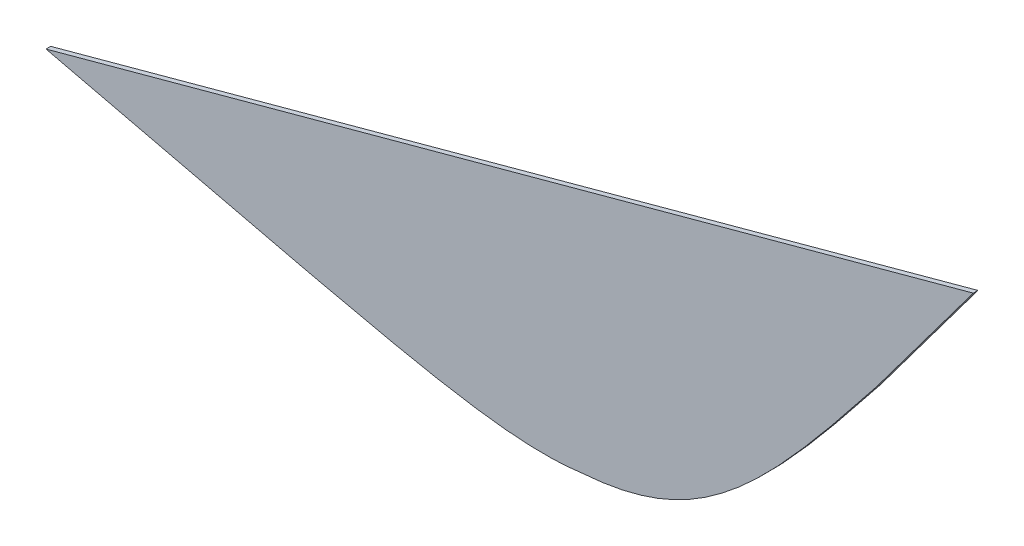
SolidWorks part; units mm, degrees
material "Сталь 3 ГОСТ 535-88"
ref_plane "Спереди" through (0, 0, 0) normal (0, 0, 1) x (1, 0, 0)
ref_plane "Сверху" through (0, 0, 0) normal (0, 1, 0) x (1, 0, 0)
ref_plane "Справа" through (0, 0, 0) normal (1, 0, 0) x (0, 0, -1)
sketch "Эскиз6" plane through (0, 0, 0) normal (0, 0, 1) x (1, 0, 0)
  line L0 (159.9974, 144.492) -> (210.3478, 69.0364)
  line L1 (226, 39.0364) -> (214.96, 39.0364) construction
  line L2 (718.4837, 179.0364) -> (700.0837, 179.0364) construction
  line L3 (-400.6671, 126.9485) -> (-400.6671, 86.2896)
  line L4 (-400.6671, 86.2896) -> (-645.3521, 86.2896)
  line L5 (-645.3521, 86.2896) -> (-645.3521, 210.6437)
  line L6 (217.4722, 117.8535) -> (217.4722, 86.841)
  line L7 (217.4722, 86.841) -> (645.9046, 86.841)
  line L8 (645.9046, 86.841) -> (645.9046, 419.9385)
  line L9 (645.9046, 419.9385) -> (589.6226, 419.9385)
  line L10 (129.7147, 135.0472) -> (134.503, 135.0472)
  line L11 (134.503, 135.0472) -> (145.3144, 146.0283)
  line L12 (145.3144, 146.0283) -> (149.5928, 146.0283)
  line L13 (170.621, 146.0283) -> (176.2959, 146.0283)
  line L14 (176.2959, 146.0283) -> (187.0167, 162.1065)
  line L15 (187.0167, 162.1065) -> (192.487, 162.1065)
  line L16 (213.5078, 162.1065) -> (217.9363, 162.1065)
  line L17 (217.9363, 162.1065) -> (223.9551, 178.9116)
  line L18 (223.9551, 178.9116) -> (227.8328, 178.9116)
  line L19 (248.8496, 178.9116) -> (253.3366, 178.9116)
  line L20 (253.3366, 178.9116) -> (259.6787, 199.2242)
  line L21 (259.6787, 199.2242) -> (263.7828, 199.2242)
  line L22 (284.7878, 199.2242) -> (289.7762, 199.2242)
  line L23 (289.7762, 199.2242) -> (293.1158, 221.4014)
  line L24 (293.1158, 221.4014) -> (296.4561, 221.4014)
  line L25 (317.4517, 221.4014) -> (322.271, 221.4014)
  line L26 (322.271, 221.4014) -> (329.3569, 250.2967)
  line L27 (329.3569, 250.2967) -> (332.468, 250.2967)
  line L28 (353.4646, 250.2967) -> (357.631, 250.2967)
  line L29 (357.631, 250.2967) -> (360.3764, 277.7773)
  line L30 (360.3764, 277.7773) -> (363.766, 277.7773)
  line L31 (384.761, 277.7773) -> (388.2696, 277.7773)
  line L32 (388.2696, 277.7773) -> (388.2696, 302.6757)
  line L33 (388.2696, 302.6757) -> (390.7857, 302.6757)
  line L34 (411.8473, 302.6757) -> (414.8074, 302.6757)
  line L35 (414.8074, 302.6757) -> (417.8424, 333.0542)
  line L36 (417.8424, 333.0542) -> (421.762, 333.0542)
  line L37 (442.8969, 333.0542) -> (446.8367, 333.0542)
  line L38 (446.8367, 333.0542) -> (450.1833, 366.5298)
  line L39 (450.1833, 366.5298) -> (453.9049, 366.5298)
  line L40 (475.1272, 366.5298) -> (479.7136, 366.5298)
  line L41 (479.7136, 366.5298) -> (483.3744, 403.1486)
  line L42 (483.3744, 403.1486) -> (488.3363, 403.1486)
  line L43 (509.572, 403.1486) -> (512.6284, 403.1486)
  line L44 (512.6284, 403.1486) -> (510.988, 431.9207)
  line L45 (510.988, 431.9207) -> (513.6642, 431.9207)
  line L46 (535.0047, 431.9207) -> (538.0588, 431.9207)
  line L47 (538.0588, 431.9207) -> (531.6588, 456.6414)
  line L48 (531.6588, 456.6414) -> (535.1524, 456.6414)
  line L49 (556.5302, 456.6414) -> (572.9497, 456.6414)
  line L50 (572.9497, 456.6414) -> (633.4819, 487.5397)
  line L51 (633.4819, 487.5397) -> (740, 487.5397)
  line L52 (740, 487.5397) -> (740, 60.0335)
  line L53 (740, 60.0335) -> (700, 60.0335)
  line L54 (700, 60.0335) -> (700, 0.0364)
  line L55 (700, 0.0364) -> (-700, 0.0364)
  line L56 (-700, 0.0364) -> (-700, 60.0335)
  line L57 (-700, 60.0335) -> (-740, 60.0335)
  line L58 (-740, 60.0335) -> (-740, 250.6437)
  line L59 (-740, 250.6437) -> (-730, 260.6437)
  line L60 (-730, 260.6437) -> (-638.0228, 260.6437)
  line L61 (-638.0228, 260.6437) -> (-612.6272, 247.9974)
  line L62 (-612.6272, 247.9974) -> (-608.3433, 247.9974)
  line L63 (-587.2113, 247.9974) -> (-583.7724, 247.9974)
  line L64 (-583.7724, 247.9974) -> (-563.198, 232.0913)
  line L65 (-563.198, 232.0913) -> (-560.5785, 232.0913)
  line L66 (-539.3589, 232.0913) -> (-535.6831, 232.0913)
  line L67 (-535.6831, 232.0913) -> (-518.1938, 218.1693)
  line L68 (-518.1938, 218.1693) -> (-515.5563, 218.1693)
  line L69 (-494.2585, 218.1192) -> (-491.1074, 218.1192)
  line L70 (-491.1074, 218.1192) -> (-478.9346, 206.3677)
  line L71 (-478.9346, 206.3677) -> (-477.0025, 206.3677)
  line L72 (-455.6816, 206.3677) -> (-451.8259, 206.3677)
  line L73 (-451.8259, 206.3677) -> (-436.7193, 193.0631)
  line L74 (-436.7193, 193.0631) -> (-433.8145, 193.0631)
  line L75 (-412.5623, 193.0631) -> (-408.8172, 193.0631)
  line L76 (-408.8172, 193.0631) -> (-390.2035, 180.5615)
  line L77 (-390.2035, 180.5615) -> (-386.7357, 180.5615)
  line L78 (-365.3543, 180.5615) -> (-361.3994, 180.5615)
  line L79 (-361.3994, 180.5615) -> (-348.9375, 170.5686)
  line L80 (-348.9375, 170.5686) -> (-346.1252, 170.5686)
  line L81 (-324.7499, 170.5686) -> (-321.4624, 170.5686)
  line L82 (-321.4624, 170.5686) -> (-307.719, 159.9631)
  line L83 (-307.719, 159.9631) -> (-304.4249, 159.9631)
  line L84 (-283.0946, 159.9631) -> (-278.741, 159.9631)
  line L85 (-278.741, 159.9631) -> (-258.7483, 149.6686)
  line L86 (-258.7483, 149.6686) -> (-254.9859, 149.6686)
  line L87 (-233.6439, 149.6686) -> (-230.797, 149.6686)
  line L88 (-230.797, 149.6686) -> (-216.8081, 140.8158)
  line L89 (-216.8081, 140.8158) -> (-214.3359, 140.8158)
  line L90 (-193.053, 140.8158) -> (-189.1396, 140.8158)
  line L91 (-189.1396, 140.8158) -> (-172.2177, 133.3984)
  line L92 (-172.2177, 133.3984) -> (-169.0298, 133.3984)
  line L93 (-147.7841, 133.3984) -> (-144.7309, 133.3984)
  line L94 (-144.7309, 133.3984) -> (-135.5541, 127.5909)
  line L95 (-135.5541, 127.5909) -> (-132.839, 127.8707)
  line L96 (-111.6873, 127.886) -> (-107.1839, 127.886)
  line L97 (-107.1839, 127.886) -> (-97.4501, 123.6194)
  line L98 (-97.4501, 123.6194) -> (-94.273, 123.6194)
  line L99 (-73.1729, 123.6194) -> (-70.5293, 123.6194)
  line L100 (-70.5293, 123.6194) -> (-58.3851, 121.2414)
  line L101 (-58.3851, 121.2414) -> (-55.027, 121.2414)
  line L102 (-33.981, 121.2414) -> (-17.5651, 120.7257)
  line L103 (3.4497, 120.7248) -> (6.5797, 120.7248)
  line L104 (6.5797, 120.7248) -> (24.5339, 122.2358)
  line L105 (24.5339, 122.2358) -> (27.2628, 122.2358)
  line L106 (48.3493, 122.2358) -> (52.6456, 122.2358)
  line L107 (52.6456, 122.2358) -> (66.9754, 126.8281)
  line L108 (66.9754, 126.8281) -> (70.0874, 126.8281)
  line L109 (91.1524, 126.8281) -> (95.4501, 126.8281)
  line L110 (95.4501, 126.8281) -> (105.3995, 135.0472)
  line L111 (105.3995, 135.0472) -> (108.7154, 135.0472)
  line L112 (119.1051, 132.5605) -> (165.9674, 87.0364)
  line L113 (80.6544, 126.6192) -> (124.3478, 87.0364)
  line L114 (37.7151, 121.1307) -> (84.3478, 87.0364)
  line L115 (187, 57.0364) -> (167.17, 57.0364) construction
  line L116 (140, 57.0364) -> (128.96, 57.0364) construction
  line L117 (100, 57.0364) -> (88.96, 57.0364) construction
  arc A0 (-645.3521, 210.6437) -> (-400.6671, 126.9485) centre (-294.2151, 837.682) ccw
  arc A1 (217.4722, 117.8535) -> (589.6226, 419.9385) centre (-115.7769, 908.672) ccw
  circle A2 centre (-690, 210.6437) radius 7.5
  circle A3 centre (-690, 86.841) radius 7.5
  circle A4 centre (690, 410.9067) radius 7.5
  circle A5 centre (690, 86.841) radius 7.5
  circle A6 centre (0, 86.841) radius 7.5
  arc A7 (149.5928, 146.0283) -> (170.4934, 143.8205) centre (159.9974, 144.492) ccw
  arc A8 (170.4934, 143.8205) -> (170.621, 146.0283) centre (160.132, 145.527) ccw
  arc A9 (192.5222, 161.4078) -> (213.5078, 162.1065) centre (203.0218, 161.553) ccw
  arc A10 (227.861, 178.3411) -> (248.8496, 178.9116) centre (238.3618, 178.3905) ccw
  arc A11 (263.788, 199.1538) -> (284.7878, 199.2242) centre (274.2878, 199.2122) ccw
  arc A12 (296.4561, 221.4014) -> (317.4517, 221.4014) centre (306.9539, 221.5851) ccw
  arc A13 (332.468, 250.2967) -> (353.4646, 250.2967) centre (342.9663, 250.0653) ccw
  arc A14 (363.766, 277.7773) -> (384.7582, 277.7092) centre (374.261, 277.4219) ccw
  arc A15 (390.7857, 302.6757) -> (411.7533, 301.8481) centre (401.2843, 302.6377) ccw
  arc A16 (421.762, 333.0542) -> (442.5956, 331.3857) centre (432.2574, 333.2017) ccw
  arc A17 (453.9049, 366.5298) -> (474.6161, 363.9727) centre (464.3993, 366.3755) ccw
  arc A18 (488.3363, 403.1486) -> (508.9775, 400.4796) centre (498.8312, 403.1622) ccw
  arc A19 (513.6642, 431.9207) -> (534.1303, 428.2462) centre (524.1492, 431.4868) ccw
  arc A20 (535.1524, 456.6414) -> (555.5133, 452.407) centre (545.6202, 455.9058) ccw
  arc A21 (-601.1014, 237.8145) -> (-587.2113, 247.9974) centre (-597.7085, 247.7513) ccw
  arc A22 (-553.2804, 222.3244) -> (-539.3589, 232.0913) centre (-549.8583, 232.2517) ccw
  arc A23 (-508.9874, 208.5183) -> (-494.2585, 218.1192) centre (-504.7606, 218.1321) ccw
  arc A24 (-469.748, 196.6324) -> (-455.6816, 206.3677) centre (-466.1821, 206.51) ccw
  arc A25 (-426.765, 184.167) -> (-412.5623, 193.0631) centre (-423.0243, 193.9804) ccw
  arc A26 (-379.6878, 171.27) -> (-365.3543, 180.5615) centre (-375.8456, 181.0444) ccw
  arc A27 (-339.5262, 160.8306) -> (-324.7499, 170.5686) centre (-335.2506, 170.4225) ccw
  arc A28 (-298.5163, 150.924) -> (-283.0946, 159.9631) centre (-293.5932, 160.1998) ccw
  arc A29 (-249.573, 140.2853) -> (-233.6439, 149.6686) centre (-244.1369, 149.2692) ccw
  arc A30 (-210.032, 132.8776) -> (-193.053, 140.8158) centre (-203.5474, 141.135) ccw
  arc A31 (-166.0837, 126.2903) -> (-147.7841, 133.3984) centre (-158.2825, 133.3164) ccw
  arc A32 (-131.5368, 123.2265) -> (-111.6873, 127.886) centre (-122.1855, 127.999) ccw
  arc A33 (-93.6949, 120.6889) -> (-73.1729, 123.6194) centre (-83.6701, 123.808) ccw
  arc A34 (-54.9241, 119.973) -> (-33.981, 121.2414) centre (-44.4786, 121.0373) ccw
  arc A35 (-17.5394, 120.0593) -> (3.4497, 120.7248) centre (-7.0426, 120.32) ccw
  arc A36 (27.2628, 122.2358) -> (48.2029, 120.439) centre (37.7151, 121.1307) ccw
  arc A37 (48.2029, 120.439) -> (48.3493, 122.2358) centre (37.8493, 122.1868) ccw
  arc A38 (70.0874, 126.8281) -> (91.0173, 124.9276) centre (80.5201, 125.5228) ccw
  arc A39 (91.0173, 124.9276) -> (91.1524, 126.8281) centre (80.6544, 126.6192) ccw
  arc A40 (108.7191, 134.67) -> (108.7137, 134.1424) centre (119.2134, 134.2996) ccw
  arc A41 (108.7137, 134.1424) -> (129.6124, 132.8403) centre (119.1051, 132.5605) ccw
  arc A42 (129.6124, 132.8403) -> (129.7095, 134.6179) centre (119.2134, 134.2996) ccw
  spline S0 degree 2 poles (129.7095, 134.6179) (129.7146, 134.7763) (129.715, 134.9349) (129.7152, 134.991) (129.7147, 135.0472) knots 5070.278971 5070.278971 5070.278971 5070.312198 5070.312198 5070.324013 5070.324013 5070.324013 weights 0.987871 0.993804 1 0.997797 0.995627
  spline S1 degree 2 poles (192.487, 162.1065) (192.49, 161.9315) (192.4988, 161.7566) (192.5076, 161.582) (192.5222, 161.4078) knots 5161.397645 5161.397645 5161.397645 5161.4343 5161.4343 5161.470885 5161.470885 5161.470885 weights 0.986649 0.993165 1 0.993178 0.986675
  spline S2 degree 2 poles (227.8328, 178.9116) (227.8352, 178.8065) (227.8397, 178.7015) (227.8473, 178.5211) (227.861, 178.3411) knots 5221.024769 5221.024769 5221.024769 5221.046824 5221.046824 5221.084599 5221.084599 5221.084599 weights 0.991891 0.995888 1 0.992956 0.986252
  spline S3 degree 2 poles (263.7828, 199.2242) (263.7854, 199.189) (263.788, 199.1538) knots 5284.416642 5284.416642 5284.416642 5284.423983 5284.423983 5284.423983 weights 0.988702 0.987387 0.986086
  spline S4 degree 2 poles (384.7582, 277.7092) (384.7597, 277.7432) (384.761, 277.7773) knots 5520.678201 5520.678201 5520.678201 5520.685284 5520.685284 5520.685284 weights 0.986308 0.987566 0.988836
  spline S5 degree 2 poles (411.7533, 301.8481) (411.7825, 302.0383) (411.8048, 302.2294) (411.8308, 302.4521) (411.8473, 302.6757) knots 5583.838669 5583.838669 5583.838669 5583.878882 5583.878882 5583.925685 5583.925685 5583.925685 weights 0.985388 0.992502 1 0.991273 0.983066
  spline S6 degree 2 poles (442.5956, 331.3857) (442.6493, 331.5886) (442.6949, 331.7935) (442.8339, 332.4178) (442.8969, 333.0542) knots 5652.338493 5652.338493 5652.338493 5652.382299 5652.382299 5652.513577 5652.513577 5652.513577 weights 0.984119 0.991832 1 0.975522 0.955135
  spline S7 degree 2 poles (474.6161, 363.9727) (474.6856, 364.1821) (474.7463, 364.3942) (475.0463, 365.4426) (475.1272, 366.5298) knots 5724.520113 5724.520113 5724.520113 5724.566104 5724.566104 5724.78602 5724.78602 5724.78602 weights 0.983351 0.991424 1 0.958994 0.92947
  spline S8 degree 2 poles (508.9775, 400.4796) (509.053, 400.6876) (509.1198, 400.8985) (509.4681, 401.9992) (509.572, 403.1486) knots 5801.380203 5801.380203 5801.380203 5801.426335 5801.426335 5801.658582 5801.658582 5801.658582 weights 0.983302 0.991398 1 0.956695 0.926195
  spline S9 degree 2 poles (534.1303, 428.2462) (534.2267, 428.4667) (534.3129, 428.6913) (534.9125, 430.2523) (535.0047, 431.9207) knots 5866.3178 5866.3178 5866.3178 5866.36787 5866.36787 5866.697512 5866.697512 5866.697512 weights 0.981923 0.990664 1 0.938534 0.902867
  spline S10 degree 2 poles (555.5133, 452.407) (555.6196, 452.6321) (555.7153, 452.8618) (556.4718, 454.6774) (556.5302, 456.6414) knots 5928.916628 5928.916628 5928.916628 5928.968377 5928.968377 5929.35179 5929.35179 5929.35179 weights 0.981337 0.990351 1 0.928508 0.891917
  spline S11 degree 2 poles (-608.3433, 247.9974) (-608.4904, 240.2809) (-601.1687, 237.8366) (-601.1352, 237.8254) (-601.1014, 237.8145) knots 8477.135492 8477.135492 8477.135492 8478.387211 8478.387211 8478.394665 8478.394665 8478.394665 weights 0.90518 0.766602 1 0.99861 0.997233
  spline S12 degree 2 poles (-560.5785, 232.0913) (-560.4128, 224.694) (-553.3887, 222.3597) (-553.3348, 222.3417) (-553.2804, 222.3244) knots 8530.653412 8530.653412 8530.653412 8531.865091 8531.865091 8531.877091 8531.877091 8531.877091 weights 0.896695 0.774068 1 0.997762 0.995559
  spline S13 degree 2 poles (-515.5563, 218.1693) (-515.498, 211.1513) (-508.9874, 208.5183) knots 8580.363906 8580.363906 8580.363906 8581.520176 8581.520176 8581.520176 weights 0.899363 0.778779 0.975604
  spline S14 degree 2 poles (-477.0025, 206.3677) (-476.8252, 199.0575) (-469.903, 196.6842) (-469.8257, 196.6577) (-469.748, 196.6324) knots 8624.356932 8624.356932 8624.356932 8625.557529 8625.557529 8625.574746 8625.574746 8625.574746 weights 0.894481 0.776135 1 0.99679 0.99365
  spline S15 degree 2 poles (-433.8145, 193.0631) (-433.1573, 186.4773) (-426.9287, 184.2247) (-426.8471, 184.1952) (-426.765, 184.167) knots 8672.457073 8672.457073 8672.457073 8673.567259 8673.567259 8673.585529 8673.585529 8673.585529 weights 0.878597 0.792993 1 0.996593 0.993266
  spline S16 degree 2 poles (-386.7357, 180.5615) (-386.3199, 173.7185) (-379.8822, 171.3396) (-379.7854, 171.3039) (-379.6878, 171.27) knots 8722.623655 8722.623655 8722.623655 8723.765117 8723.765117 8723.78682 8723.78682 8723.78682 weights 0.883653 0.787161 1 0.995953 0.992018
  spline S17 degree 2 poles (-346.1252, 170.5686) (-346.1152, 163.6154) (-339.7049, 160.9042) (-339.616, 160.8666) (-339.5262, 160.8306) knots 8766.475221 8766.475221 8766.475221 8767.629472 8767.629472 8767.649796 8767.649796 8767.649796 weights 0.885854 0.784777 1 0.99621 0.992518
  spline S18 degree 2 poles (-304.4249, 159.9631) (-304.1826, 153.7999) (-298.6789, 151.0048) (-298.598, 150.9637) (-298.5163, 150.924) knots 8812.636654 8812.636654 8812.636654 8813.685999 8813.685999 8813.705117 8813.705117 8813.705117 weights 0.870093 0.804337 1 0.996435 0.992957
  spline S19 degree 2 poles (-254.9859, 149.6686) (-255.0988, 143.4833) (-249.7406, 140.3803) (-249.6573, 140.332) (-249.573, 140.2853) knots 8865.691142 8865.691142 8865.691142 8866.742975 8866.742975 8866.763254 8866.763254 8866.763254 weights 0.870407 0.803874 1 0.996219 0.992535
  spline S20 degree 2 poles (-214.3359, 140.8158) (-214.0777, 135.9353) (-210.1773, 132.9855) (-210.1051, 132.931) (-210.032, 132.8776) knots 8911.244919 8911.244919 8911.244919 8912.111469 8912.111469 8912.130525 8912.130525 8912.130525 weights 0.855117 0.838422 1 0.996447 0.99298
  spline S21 degree 2 poles (-169.0298, 133.3984) (-168.9561, 129.3667) (-166.204, 126.4172) (-166.1444, 126.3532) (-166.0837, 126.2903) knots 8960.870513 8960.870513 8960.870513 8961.606208 8961.606208 8961.624618 8961.624618 8961.624618 weights 0.85414 0.862821 1 0.996567 0.993215
  spline S22 degree 2 poles (-132.839, 127.8707) (-132.7387, 125.4836) (-131.6168, 123.3739) (-131.5774, 123.2999) (-131.5368, 123.2265) knots 9003.634789 9003.634789 9003.634789 9004.09641 9004.09641 9004.114076 9004.114076 9004.114076 weights 0.878441 0.913925 1 0.996706 0.993486
  spline S23 degree 2 poles (-94.273, 123.6194) (-94.1989, 122.205) (-93.7534, 120.8605) (-93.7249, 120.7744) (-93.6949, 120.6889) knots 9050.338042 9050.338042 9050.338042 9050.621567 9050.621567 9050.640664 9050.640664 9050.640664 weights 0.913351 0.947133 1 0.996439 0.992965
  spline S24 degree 2 poles (-55.027, 121.2414) (-55.0161, 120.7062) (-54.9509, 120.175) (-54.9384, 120.0738) (-54.9241, 119.973) knots 9098.644621 9098.644621 9098.644621 9098.755383 9098.755383 9098.776823 9098.776823 9098.776823 weights 0.961607 0.979347 1 0.996002 0.992114
  spline S25 degree 2 poles (-17.5651, 120.7257) (-17.5636, 120.5074) (-17.5531, 120.2894) (-17.5475, 120.1743) (-17.5394, 120.0593) knots 9147.324142 9147.324142 9147.324142 9147.369854 9147.369854 9147.394091 9147.394091 9147.394091 weights 0.983449 0.991476 1 0.995481 0.991101
  spline S26 degree 2 poles (108.7154, 135.0472) (108.7152, 135.0171) (108.7151, 134.987) (108.7147, 134.8284) (108.7191, 134.67) knots 9318.268201 9318.268201 9318.268201 9318.274542 9318.274542 9318.30777 9318.30777 9318.30777 weights 0.997645 0.998818 1 0.993804 0.987871
  text T0 "1" font "ARIAL" height 30
  text T1 "1" font "ARIAL" height 50
  text T2 "2" font "ARIAL" height 30
  text T3 "1" font "ARIAL" height 30
  text T4 "1" font "ARIAL" height 30
sketch "Эскиз8" plane through (0, 0, 0) normal (0, 0, 1) x (1, 0, 0)
  circle B0 centre (-597.7085, 247.7513) radius 10.5
  circle B1 centre (-549.8583, 232.2517) radius 10.5
  circle B2 centre (-504.7606, 218.1321) radius 10.5
  circle B3 centre (-466.1821, 206.51) radius 10.5
  circle B4 centre (-423.0243, 193.9804) radius 10.5
  circle B5 centre (-375.8456, 181.0444) radius 10.5
  circle B6 centre (-335.2506, 170.4225) radius 10.5
  circle B7 centre (-293.5932, 160.1998) radius 10.5
  circle B8 centre (-244.1369, 149.2692) radius 10.5
  circle B9 centre (-203.5474, 141.135) radius 10.5
  circle B10 centre (-158.2825, 133.3164) radius 10.5
  circle B11 centre (-122.1855, 127.999) radius 10.5
  circle B12 centre (-83.6701, 123.808) radius 10.5
  circle B13 centre (-44.4786, 121.0373) radius 10.5
  circle B14 centre (-7.0426, 120.32) radius 10.5
  circle B15 centre (37.665, 120.1307) radius 10.5
  circle B16 centre (80.5201, 124.5228) radius 10.5
  circle B17 centre (119.1051, 130.5605) radius 10.5
  circle B18 centre (159.9974, 143.492) radius 10.5
  circle B19 centre (203.0218, 161.553) radius 10.5
  circle B20 centre (238.3618, 178.3905) radius 10.5
  circle B21 centre (274.2878, 199.2122) radius 10.5
  circle B22 centre (306.9539, 221.5851) radius 10.5
  circle B23 centre (342.9663, 250.0653) radius 10.5
  circle B24 centre (374.261, 277.4219) radius 10.5
  circle B25 centre (401.2843, 302.6377) radius 10.5
  circle B26 centre (432.2574, 333.2017) radius 10.5
  circle B27 centre (464.3993, 366.3755) radius 10.5
  circle B28 centre (498.8312, 403.1622) radius 10.5
  circle B29 centre (524.1492, 431.4868) radius 10.5
  circle B30 centre (545.6202, 455.9058) radius 10.5
sketch_block_instance "Блок2-1"
sketch_block "Блок2" parameters "D1"=21
sketch_block_instance "Блок2-2"
sketch_block_instance "Блок2-3"
sketch_block_instance "Блок2-4"
sketch_block_instance "Блок2-5"
sketch_block_instance "Блок2-6"
sketch_block_instance "Блок2-7"
sketch_block_instance "Блок2-8"
sketch_block_instance "Блок2-9"
sketch_block_instance "Блок2-10"
sketch_block_instance "Блок2-11"
sketch_block_instance "Блок2-12"
sketch_block_instance "Блок2-13"
sketch_block_instance "Блок2-14"
sketch_block_instance "Блок2-15"
sketch_block_instance "Блок2-16"
sketch_block_instance "Блок2-17"
sketch_block_instance "Блок2-18"
sketch_block_instance "Блок2-19"
sketch_block_instance "Блок2-20"
sketch_block_instance "Блок2-21"
sketch_block_instance "Блок2-22"
sketch_block_instance "Блок2-23"
sketch_block_instance "Блок2-24"
sketch_block_instance "Блок2-25"
sketch_block_instance "Блок2-26"
sketch_block_instance "Блок2-27"
sketch_block_instance "Блок2-28"
sketch_block_instance "Блок2-29"
sketch_block_instance "Блок2-30"
sketch_block_instance "Блок2-31"
sketch "Эскиз9" plane through (0, 0, 0) normal (0, 0, 1) x (1, 0, 0)
  circle A1 centre (-83.6701, 123.808) radius 10.5 construction
  circle A2 centre (-44.4786, 121.0373) radius 10.5 construction
  circle A22 centre (-549.8583, 232.2517) radius 10.5 construction
  circle A23 centre (-504.7606, 218.1321) radius 10.5 construction
  circle A24 centre (-466.1821, 206.51) radius 10.5 construction
  circle A25 centre (-423.0243, 193.9804) radius 10.5 construction
  circle A26 centre (-375.8456, 181.0444) radius 10.5 construction
  circle A27 centre (-335.2506, 170.4225) radius 10.5 construction
  circle A28 centre (-244.1369, 149.2692) radius 10.5 construction
  circle A29 centre (-203.5474, 141.135) radius 10.5 construction
  circle A30 centre (-158.2825, 133.3164) radius 10.5 construction
  circle A31 centre (-122.1855, 127.999) radius 10.5 construction
  circle A50 centre (545.6202, 455.9058) radius 10.5 construction
  circle A51 centre (-597.7085, 247.7513) radius 10.5 construction
  circle A59 centre (-7.0426, 120.32) radius 10.5 construction
  spline S0 degree 3 poles (-595.2914, 257.9693) (-578.752, 254.0568) (-548.0164, 241.9687) (-503.8382, 228.8781) (-461.7604, 216.0535) (-418.9314, 203.5998) (-375.3728, 191.7234) (-316.2363, 176.1262) (-258.5784, 162.8202) (-200.9016, 151.0535) (-157.0695, 143.7377) (-135.597, 140.1396) (-120.9655, 138.4279) knots 0 0 0 0 0.040186 0.076884 0.108413 0.143483 0.181679 0.214438 0.2873 0.319704 0.35481 0.38534 0.38534 0.38534 0.38534
  spline S1 degree 3 poles (-43.2749, 131.4681) (-27.5504, 130.8734) (-14.9741, 131.2834) (42.1785, 129.291) (79.1583, 135.3239) (119.8903, 140.0725) (157.9174, 153.433) (196.5016, 169.9126) (234.4247, 187.4635) (268.4205, 207.3659) (302.7434, 230.8872) (335.3877, 256.9831) (366.2323, 284.0437) (399.6333, 315.2407) (429.3089, 344.9471) (461.4341, 378.4538) (488.7433, 406.9464) (514.3779, 437.2939) (531.1004, 453.4004) (536.9941, 461.8924) knots 0.446618 0.446618 0.446618 0.446618 0.484644 0.5172 0.553417 0.579538 0.611819 0.647943 0.6781 0.709911 0.74035 0.77578 0.808015 0.836728 0.883135 0.906626 0.94579 0.975783 1 1 1 1
  spline S2 degree 3 poles (-120.9655, 138.4279) (-96.8749, 135.6096) (-68.5215, 132.4228) (-43.2749, 131.4681) knots 0 0 0 0 1 1 1 1
sketch "Эскиз10" plane through (0, 0, 0) normal (0, 0, 1) x (1, 0, 0)
  line L0 (-589.5363, 282.2979) -> (-589.5363, 976.1465)
  line L1 (-589.5363, 976.1465) -> (516.4557, 976.1465)
  line L2 (516.4557, 976.1465) -> (516.4557, 476.1465)
  spline S0 degree 3 poles (-1623.0802, -2540.9145) (-855.0176, 430.0741) (-695.5367, 285.681) (-503.8382, 228.8781) (-461.7604, 216.0535) (-418.9314, 203.5998) (-375.3728, 191.7234) (-316.2363, 176.1262) (-258.5784, 162.8202) (-200.9016, 151.0535) (-63.5486, 128.1286) (-78.6887, 130.4064) (2875.4364, -4.8346) knots -0.362015 -0.362015 -0.362015 -0.362015 0.040186 0.076884 0.108413 0.143483 0.181679 0.214438 0.2873 0.319704 0.35481 0.594519 0.594519 0.594519 0.594519 only from (-595.2914, 257.9693) to (-120.9655, 138.4279) construction
  spline S1 degree 3 poles (-3033.6281, 370.2521) (89.4783, 115.9564) (-117.3878, 134.8536) (42.1785, 129.291) (79.1583, 135.3239) (119.8903, 140.0725) (157.9174, 153.433) (196.5016, 169.9126) (234.4247, 187.4635) (268.4205, 207.3659) (302.7434, 230.8872) (335.3877, 256.9831) (366.2323, 284.0437) (399.6333, 315.2407) (429.3089, 344.9471) (461.4341, 378.4538) (488.7433, 406.9464) (579.4919, 514.3791) (712.6391, 565.3832) (-1569.5064, 2586.606) knots 0.255241 0.255241 0.255241 0.255241 0.484644 0.5172 0.553417 0.579538 0.611819 0.647943 0.6781 0.709911 0.74035 0.77578 0.808015 0.836728 0.883135 0.906626 0.94579 0.975783 1.237176 1.237176 1.237176 1.237176 only from (-43.2749, 131.4681) to (536.9941, 461.8924) construction
  spline S2 degree 3 poles (2724.0188, -812.827) (-3652.4377, 1274.5768) (3442.2979, -1123.3778) (-2739.6676, 1431.8612) knots -7.16141 -7.16141 -7.16141 -7.16141 8.206534 8.206534 8.206534 8.206534 only from (-120.9655, 138.4279) to (-43.2749, 131.4681) construction
  spline S3 degree 3 poles (-43.2749, 131.4681) (-27.5504, 130.8734) (-14.9741, 131.2834) (42.1785, 129.291) (79.1583, 135.3239) (119.8903, 140.0725) (157.9174, 153.433) (196.5016, 169.9126) (234.4247, 187.4635) (268.4205, 207.3659) (302.7434, 230.8872) (335.3877, 256.9831) (366.2323, 284.0437) (399.6333, 315.2407) (429.3089, 344.9471) (461.4341, 378.4538) (488.7433, 406.9464) (514.3779, 437.2939) (531.1004, 453.4004) (536.9941, 461.8924) knots 0.446618 0.446618 0.446618 0.446618 0.484644 0.5172 0.553417 0.579538 0.611819 0.647943 0.6781 0.709911 0.74035 0.77578 0.808015 0.836728 0.883135 0.906626 0.94579 0.975783 1 1 1 1
  spline S4 degree 3 poles (-120.9655, 138.4279) (-96.8749, 135.6096) (-68.5215, 132.4228) (-43.2749, 131.4681) knots 0 0 0 0 1 1 1 1
  spline S5 degree 3 poles (-595.2914, 257.9693) (-578.752, 254.0568) (-548.0164, 241.9687) (-503.8382, 228.8781) (-461.7604, 216.0535) (-418.9314, 203.5998) (-375.3728, 191.7234) (-316.2363, 176.1262) (-258.5784, 162.8202) (-200.9016, 151.0535) (-157.0695, 143.7377) (-135.597, 140.1396) (-120.9655, 138.4279) knots 0 0 0 0 0.040186 0.076884 0.108413 0.143483 0.181679 0.214438 0.2873 0.319704 0.35481 0.38534 0.38534 0.38534 0.38534
  spline S6 degree 1 poles (-589.5363, 282.2979) (-118.0606, 163.2586) knots 0 0 1 1 construction
  spline S7 degree 1 poles (-118.0606, 163.2586) (-42.3302, 156.4502) knots 0 0 1 1 construction
  spline S8 degree 1 poles (-42.3302, 156.4502) (516.4557, 476.1465) knots 0 0 1 1 construction
  spline S9 degree 3 poles (-589.5363, 282.2979) (-588.1303, 281.9653) (-585.3138, 281.2668) (-579.8031, 279.7854) (-573.0725, 277.7876) (-565.2478, 275.2433) (-555.1224, 271.7569) (-545.3985, 268.2629) (-536.1023, 265.0533) (-526.7253, 261.9583) (-514.8112, 258.2259) (-500.243, 253.8432) (-485.4304, 249.3866) (-470.7288, 244.934) (-456.0803, 240.5302) (-436.5779, 234.7646) (-412.1648, 227.7437) (-382.7446, 219.6377) (-353.1631, 211.7007) (-323.7111, 204.0459) (-294.0732, 196.8033) (-269.3019, 191.0904) (-249.5269, 186.7236) (-234.7248, 183.5469) (-220.0131, 180.4851) (-205.2188, 177.5463) (-190.0718, 174.7296) (-174.5613, 172.0218) (-162.0511, 169.9131) (-152.5905, 168.3317) (-145.9456, 167.2212) (-139.5249, 166.1834) (-134.0814, 165.3582) (-129.5028, 164.7099) (-125.9156, 164.2269) (-122.7575, 163.8242) (-120.1233, 163.5022) (-118.743, 163.3384) (-118.0606, 163.2586) knots 0 0 0 0 0.00301 0.006021 0.012042 0.018063 0.024084 0.036126 0.042147 0.048167 0.060209 0.072251 0.084293 0.096335 0.108377 0.120419 0.144502 0.168586 0.19267 0.216754 0.240837 0.264921 0.276963 0.289005 0.301047 0.313089 0.32513 0.337172 0.349214 0.355235 0.361256 0.367277 0.373298 0.376308 0.379319 0.382329 0.383835 0.38534 0.38534 0.38534 0.38534
  spline S10 degree 3 poles (-118.0606, 163.2586) (-116.5466, 163.0814) (-113.5374, 162.7304) (-107.3669, 162.018) (-99.5051, 161.1302) (-89.8839, 160.0949) (-80.1727, 159.1204) (-70.4604, 158.2363) (-60.838, 157.4719) (-52.9834, 156.9588) (-46.8285, 156.6359) (-43.8371, 156.5072) (-42.3302, 156.4502) knots 0 0 0 0 0.0625 0.125 0.25 0.375 0.5 0.625 0.75 0.875 0.9375 1 1 1 1
  spline S11 degree 3 poles (-42.3302, 156.4502) (-41.9049, 156.4341) (-41.0439, 156.4023) (-39.4043, 156.3447) (-37.4447, 156.2811) (-35.236, 156.2175) (-32.4481, 156.1475) (-29.2097, 156.0841) (-25.5488, 156.0347) (-21.9482, 156.0011) (-17.0165, 155.9617) (-10.298, 155.9002) (-0.1724, 155.6792) (11.357, 155.4062) (23.4904, 155.2785) (33.3532, 155.427) (40.5481, 155.7705) (47.5543, 156.2663) (56.03, 157.1281) (66.1885, 158.4471) (74.901, 159.6827) (82.2508, 160.6847) (89.5116, 161.6361) (98.2858, 162.8203) (106.5867, 164.1987) (112.7706, 165.4916) (118.9449, 166.9939) (126.771, 169.2577) (136.328, 172.4924) (146.1182, 176.1546) (159.3701, 181.3808) (172.536, 186.9089) (185.74, 192.7033) (198.935, 198.6164) (211.7516, 204.6289) (224.0782, 210.9335) (236.2508, 217.5775) (251.2842, 226.5119) (269.0006, 238.0457) (286.2162, 250.2321) (303.0341, 263.1391) (319.6169, 276.704) (341.4159, 295.4168) (362.7517, 314.8724) (383.6326, 334.866) (399.1035, 350.1378) (414.4189, 365.6413) (429.5886, 381.3536) (444.9075, 397.327) (457.4196, 410.4716) (465.9321, 419.6889) (470.7162, 424.9707) (475.4336, 430.2616) (481.4268, 437.1093) (487.6233, 444.1607) (492.7704, 449.8755) (496.7378, 454.1836) (500.8457, 458.497) (504.675, 462.4511) (508.211, 466.1699) (511.387, 469.6764) (513.6988, 472.4429) (515.3479, 474.5891) (516.0885, 475.6173) (516.4557, 476.1465) knots 0.446618 0.446618 0.446618 0.446618 0.447698 0.448779 0.450941 0.453102 0.455264 0.459587 0.463911 0.468234 0.472557 0.481204 0.489851 0.498497 0.507144 0.51579 0.520114 0.524437 0.533084 0.54173 0.550377 0.5547 0.559023 0.56767 0.576317 0.58064 0.584963 0.59361 0.602256 0.610903 0.61955 0.636843 0.645489 0.654136 0.671429 0.680076 0.688722 0.706016 0.723309 0.740602 0.757895 0.775188 0.792482 0.827068 0.844361 0.861654 0.878948 0.896241 0.913534 0.930827 0.939474 0.943797 0.94812 0.956767 0.965414 0.969737 0.97406 0.978383 0.982707 0.98703 0.991353 0.995677 0.997838 1 1 1 1
  dimension "D2" = 500
  dimension "D1" = 25
sketch "Эскиз11" plane through (0, 0, 0) normal (0, 0, 1) x (1, 0, 0)
  line L1 (-589.5363, 976.1465) -> (516.4557, 976.1465) construction
  line L2 (-589.5363, 282.2979) -> (-589.5363, 976.1465) construction
  line L3 (636.4639, 976.1465) -> (700.2056, 770.0853)
  line L4 (-589.5363, 976.1465) -> (636.4639, 976.1465)
  line L5 (-589.5363, 282.2979) -> (-589.5363, 976.1465)
  line L6 (700.2056, 770.0853) -> (141.8482, 128.2348) construction
  line L7 (141.8482, 128.2348) -> (116.5614, 120.1222) construction
  line L8 (116.5614, 120.1222) -> (-589.5363, 282.2979) construction
  spline S0 degree 3 poles (2185.315, -855.0691) (-790.7964, 288.3521) (-661.5399, 301.7572) (-579.8031, 279.7854) (-573.0725, 277.7876) (-565.2478, 275.2433) (-555.1224, 271.7569) (-545.3985, 268.2629) (-536.1023, 265.0533) (-526.7253, 261.9583) (-514.8112, 258.2259) (-500.243, 253.8432) (-485.4304, 249.3866) (-470.7288, 244.934) (-456.0803, 240.5302) (-436.5779, 234.7646) (-412.1648, 227.7437) (-382.7446, 219.6377) (-353.1631, 211.7007) (-323.7111, 204.0459) (-294.0732, 196.8033) (-269.3019, 191.0904) (-249.5269, 186.7236) (-234.7248, 183.5469) (-220.0131, 180.4851) (-205.2188, 177.5463) (-190.0718, 174.7296) (-174.5613, 172.0218) (-162.0511, 169.9131) (-152.5905, 168.3317) (-145.9456, 167.2212) (-139.5249, 166.1834) (-134.0814, 165.3582) (-129.5028, 164.7099) (-125.9156, 164.2269) (-122.7575, 163.8242) (-86.871, 159.4387) (-8.8021, 153.2319) (-3095.7299, 527.4773) knots -0.166568 -0.166568 -0.166568 -0.166568 0.00301 0.006021 0.012042 0.018063 0.024084 0.036126 0.042147 0.048167 0.060209 0.072251 0.084293 0.096335 0.108377 0.120419 0.144502 0.168586 0.19267 0.216754 0.240837 0.264921 0.276963 0.289005 0.301047 0.313089 0.32513 0.337172 0.349214 0.355235 0.361256 0.367277 0.373298 0.376308 0.379319 0.382329 0.383835 0.461343 0.461343 0.461343 0.461343 only from (-589.5363, 282.2979) to (-118.0606, 163.2586) construction
  spline S1 degree 3 poles (-3101.6275, 475.5191) (-214.3341, 176.409) (-184.0599, 170.8729) (-107.3669, 162.018) (-99.5051, 161.1302) (-89.8839, 160.0949) (-80.1727, 159.1204) (-70.4604, 158.2363) (-60.838, 157.4719) (-52.9834, 156.9588) (20.4597, 153.1062) (45.8297, 166.5078) (2957.3866, 125.2066) knots -2.857217 -2.857217 -2.857217 -2.857217 0.0625 0.125 0.25 0.375 0.5 0.625 0.75 0.875 0.9375 3.733106 3.733106 3.733106 3.733106 only from (-118.0606, 163.2586) to (-42.3302, 156.4502) construction
  spline S2 degree 3 poles (2955.1716, 50.1604) (-126.5063, 160.7892) (-64.8276, 157.2388) (-39.4043, 156.3447) (-37.4447, 156.2811) (-35.236, 156.2175) (-32.4481, 156.1475) (-29.2097, 156.0841) (-25.5488, 156.0347) (-21.9482, 156.0011) (-17.0165, 155.9617) (-10.298, 155.9002) (-0.1724, 155.6792) (11.357, 155.4062) (23.4904, 155.2785) (33.3532, 155.427) (40.5481, 155.7705) (47.5543, 156.2663) (56.03, 157.1281) (66.1885, 158.4471) (74.901, 159.6827) (82.2508, 160.6847) (89.5116, 161.6361) (98.2858, 162.8203) (106.5867, 164.1987) (112.7706, 165.4916) (118.9449, 166.9939) (126.771, 169.2577) (136.328, 172.4924) (146.1182, 176.1546) (159.3701, 181.3808) (172.536, 186.9089) (185.74, 192.7033) (198.935, 198.6164) (211.7516, 204.6289) (224.0782, 210.9335) (236.2508, 217.5775) (251.2842, 226.5119) (269.0006, 238.0457) (286.2162, 250.2321) (303.0341, 263.1391) (319.6169, 276.704) (341.4159, 295.4168) (362.7517, 314.8724) (383.6326, 334.866) (399.1035, 350.1378) (414.4189, 365.6413) (429.5886, 381.3536) (444.9075, 397.327) (457.4196, 410.4716) (465.9321, 419.6889) (470.7162, 424.9707) (475.4336, 430.2616) (481.4268, 437.1093) (487.6233, 444.1607) (492.7704, 449.8755) (496.7378, 454.1836) (500.8457, 458.497) (504.675, 462.4511) (508.211, 466.1699) (511.387, 469.6764) (513.6988, 472.4429) (533.7597, 498.5513) (507.2561, 499.0962) (2154.5227, 2988.9754) knots 0.383905 0.383905 0.383905 0.383905 0.447698 0.448779 0.450941 0.453102 0.455264 0.459587 0.463911 0.468234 0.472557 0.481204 0.489851 0.498497 0.507144 0.51579 0.520114 0.524437 0.533084 0.54173 0.550377 0.5547 0.559023 0.56767 0.576317 0.58064 0.584963 0.59361 0.602256 0.610903 0.61955 0.636843 0.645489 0.654136 0.671429 0.680076 0.688722 0.706016 0.723309 0.740602 0.757895 0.775188 0.792482 0.827068 0.844361 0.861654 0.878948 0.896241 0.913534 0.930827 0.939474 0.943797 0.94812 0.956767 0.965414 0.969737 0.97406 0.978383 0.982707 0.98703 0.991353 0.995677 0.997838 1.096537 1.096537 1.096537 1.096537 only from (-42.3302, 156.4502) to (516.4557, 476.1465) construction
  spline S3 degree 3 poles (-589.5363, 282.2979) (-588.1303, 281.9653) (-585.3138, 281.2668) (-579.8031, 279.7854) (-573.0725, 277.7876) (-565.2478, 275.2433) (-555.1224, 271.7569) (-545.3985, 268.2629) (-536.1023, 265.0533) (-526.7253, 261.9583) (-514.8112, 258.2259) (-500.243, 253.8432) (-485.4304, 249.3866) (-470.7288, 244.934) (-456.0803, 240.5302) (-436.5779, 234.7646) (-412.1648, 227.7437) (-382.7446, 219.6377) (-353.1631, 211.7007) (-323.7111, 204.0459) (-294.0732, 196.8033) (-269.3019, 191.0904) (-249.5269, 186.7236) (-234.7248, 183.5469) (-220.0131, 180.4851) (-205.2188, 177.5463) (-190.0718, 174.7296) (-174.5613, 172.0218) (-162.0511, 169.9131) (-152.5905, 168.3317) (-145.9456, 167.2212) (-139.5249, 166.1834) (-134.0814, 165.3582) (-129.5028, 164.7099) (-125.9156, 164.2269) (-122.7575, 163.8242) (-120.1233, 163.5022) (-118.743, 163.3384) (-118.0606, 163.2586) knots 0 0 0 0 0.00301 0.006021 0.012042 0.018063 0.024084 0.036126 0.042147 0.048167 0.060209 0.072251 0.084293 0.096335 0.108377 0.120419 0.144502 0.168586 0.19267 0.216754 0.240837 0.264921 0.276963 0.289005 0.301047 0.313089 0.32513 0.337172 0.349214 0.355235 0.361256 0.367277 0.373298 0.376308 0.379319 0.382329 0.383835 0.38534 0.38534 0.38534 0.38534 construction
  spline S4 degree 3 poles (-118.0606, 163.2586) (-116.5466, 163.0814) (-113.5374, 162.7304) (-107.3669, 162.018) (-99.5051, 161.1302) (-89.8839, 160.0949) (-80.1727, 159.1204) (-70.4604, 158.2363) (-60.838, 157.4719) (-52.9834, 156.9588) (-46.8285, 156.6359) (-43.8371, 156.5072) (-42.3302, 156.4502) knots 0 0 0 0 0.0625 0.125 0.25 0.375 0.5 0.625 0.75 0.875 0.9375 1 1 1 1 construction
  spline S5 degree 3 poles (-42.3302, 156.4502) (-41.9049, 156.4341) (-41.0439, 156.4023) (-39.4043, 156.3447) (-37.4447, 156.2811) (-35.236, 156.2175) (-32.4481, 156.1475) (-29.2097, 156.0841) (-25.5488, 156.0347) (-21.9482, 156.0011) (-17.0165, 155.9617) (-10.298, 155.9002) (-0.1724, 155.6792) (11.357, 155.4062) (23.4904, 155.2785) (33.3532, 155.427) (40.5481, 155.7705) (47.5543, 156.2663) (56.03, 157.1281) (66.1885, 158.4471) (74.901, 159.6827) (82.2508, 160.6847) (89.5116, 161.6361) (98.2858, 162.8203) (106.5867, 164.1987) (112.7706, 165.4916) (118.9449, 166.9939) (126.771, 169.2577) (136.328, 172.4924) (146.1182, 176.1546) (159.3701, 181.3808) (172.536, 186.9089) (185.74, 192.7033) (198.935, 198.6164) (211.7516, 204.6289) (224.0782, 210.9335) (236.2508, 217.5775) (251.2842, 226.5119) (269.0006, 238.0457) (286.2162, 250.2321) (303.0341, 263.1391) (319.6169, 276.704) (341.4159, 295.4168) (362.7517, 314.8724) (383.6326, 334.866) (399.1035, 350.1378) (414.4189, 365.6413) (429.5886, 381.3536) (444.9075, 397.327) (457.4196, 410.4716) (465.9321, 419.6889) (470.7162, 424.9707) (475.4336, 430.2616) (481.4268, 437.1093) (487.6233, 444.1607) (492.7704, 449.8755) (496.7378, 454.1836) (500.8457, 458.497) (504.675, 462.4511) (508.211, 466.1699) (511.387, 469.6764) (513.6988, 472.4429) (523.9634, 485.8019) (522.3881, 492.1898) (700.2056, 770.0853) knots 0.446618 0.446618 0.446618 0.446618 0.447698 0.448779 0.450941 0.453102 0.455264 0.459587 0.463911 0.468234 0.472557 0.481204 0.489851 0.498497 0.507144 0.51579 0.520114 0.524437 0.533084 0.54173 0.550377 0.5547 0.559023 0.56767 0.576317 0.58064 0.584963 0.59361 0.602256 0.610903 0.61955 0.636843 0.645489 0.654136 0.671429 0.680076 0.688722 0.706016 0.723309 0.740602 0.757895 0.775188 0.792482 0.827068 0.844361 0.861654 0.878948 0.896241 0.913534 0.930827 0.939474 0.943797 0.94812 0.956767 0.965414 0.969737 0.97406 0.978383 0.982707 0.98703 0.991353 0.995677 0.997838 1.045173 1.045173 1.045173 1.045173 construction
  spline S6 degree 3 poles (700.2056, 770.0853) (141.8482, 128.2348) (116.5614, 120.1222) (-589.5363, 282.2979) knots 0 0 0 0 1 1 1 1
extrude "Бобышка-Вытянуть1" add sketch "Эскиз11" along normal mid plane 10
sketch "Эскиз12" plane through (0, 0, 0) normal (0, 0, 1) x (1, 0, 0)
  line L8 (-700.7002, 528.9421) -> (706.1673, 911.6736)
  line L9 (-820.6825, 1079.9722) -> (-700.7002, 528.9421)
  line L10 (340.9036, 1222.5254) -> (-820.6825, 1079.9722)
  line L11 (706.1673, 911.6736) -> (340.9036, 1222.5254)
extrude "Вырез-Вытянуть1" cut sketch "Эскиз12" against normal through all and the other way through all
sketch "Эскиз14" plane through (0, 0, -5) normal (0, 0, -1) x (-1, 0, 0)
  line L2 (-612.1586, 782.4646) -> (-585.9081, 878.9577) construction
  line L7 (-637.7856, 672.3124) -> (-248.934, 179.4356) construction
  line L10 (1133.9413, 411.081) -> (589.5363, 282.2979)
  line L11 (-660.2699, 899.1874) -> (-844.9171, 949.4198)
  line L13 (589.5363, 282.2979) -> (589.5363, 559.1837)
  line L14 (589.5363, 559.1837) -> (-660.2699, 899.1874)
  line L15 (-660.2699, 899.1874) -> (-700.2056, 770.0853)
  line L17 (1133.9413, 411.081) -> (-660.2699, 899.1874)
  line L19 (-248.934, 179.4356) -> (-152.9666, 110.5576) construction
  line L20 (-152.9666, 110.5576) -> (589.5363, 282.2979) construction
  line L21 (-637.7856, 672.3124) -> (-844.9171, 949.4198)
  spline S0 degree 3 poles (-637.7856, 672.3124) (-248.934, 179.4356) (-152.9666, 110.5576) (589.5363, 282.2979) knots 0 0 0 0 1 1 1 1
  spline S1 degree 3 poles (-2059.6049, 2236.4529) (752.9514, -576.9824) (-1142.7775, 197.5708) (2558.8072, 625.5217) knots -0.492867 -0.492867 -0.492867 -0.492867 1.547143 1.547143 1.547143 1.547143 only from (-700.2056, 770.0853) to (589.5363, 282.2979)
  spline S2 degree 3 poles (-635.6659, 696.0551) (-138.7347, 127.8582) (-88.3093, 126.6111) (589.5363, 282.2979) knots 0.040012 0.040012 0.040012 0.040012 1 1 1 1 construction
  dimension "D1" = 0
extrude "Бобышка-Вытянуть2" add sketch "Эскиз14" against normal up to surface (10 mm away) up to face at (-115.867, 566.7152, 5)
ref_plane "Плоскость1" through (0, 976.1465, 0) normal (0, 1, 0) x (1, 0, 0)
delete or keep bodies "Тело-Удалить/Сохранить 1" type delete bodies bodies 108
